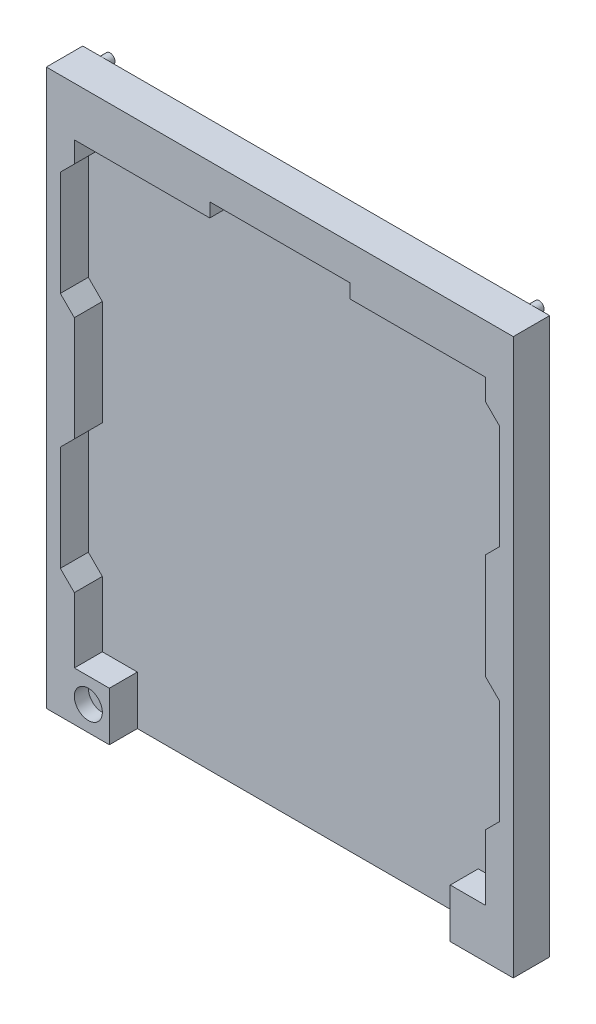
SolidWorks part; units mm, degrees
ref_plane "Plan de face" through (0, 0, 0) normal (0, 0, 1) x (1, 0, 0)
ref_plane "Plan de dessus" through (0, 0, 0) normal (0, 1, 0) x (1, 0, 0)
ref_plane "Plan de droite" through (0, 0, 0) normal (1, 0, 0) x (0, 0, -1)
sketch "Esquisse1" plane through (0, 0, 0) normal (0, 0, 1) x (1, 0, 0)
  line L1 (-33.34, 39.66) -> (0, 39.66)
  line L2 (-33.34, 39.66) -> (-33.34, 0)
  line L3 (-33.34, 0) -> (0, 0)
  line L4 (0, 39.66) -> (0, 0)
  dimension "D1" = 39.66
  dimension "D2" = 33.34
extrude "Boss.-Extru.1" add sketch "Esquisse1" along normal blind 0.6
sketch "Esquisse2" plane through (0, 0, 0.6) normal (0, 0, 1) x (1, 0, 0)
  line L0 (-31.34, 36.16) -> (-21.67, 36.16)
  line L1 (-33.34, 39.66) -> (0, 39.66)
  line L2 (-33.34, 39.66) -> (-33.34, 0)
  line L3 (-33.34, 0) -> (0, 0)
  line L4 (0, 39.66) -> (0, 0)
  line L5 (-21.67, 36.16) -> (-21.67, 37.16)
  line L6 (-2, 36.16) -> (-11.67, 36.16)
  line L7 (-11.67, 36.16) -> (-11.67, 37.16)
  line L8 (-11.67, 37.16) -> (-21.67, 37.16)
  line L9 (-2, 36.16) -> (-2, 34.66)
  line L10 (-31.34, 36.16) -> (-31.34, 34.66)
  line L11 (-1, 33.66) -> (-1, 26.16)
  line L12 (-31.34, 25.16) -> (-32.34, 26.16)
  line L13 (-2, 25.16) -> (-2, 17.66)
  line L14 (-2, 17.66) -> (-1, 16.66)
  line L15 (-1, 16.66) -> (-1, 9.16)
  line L16 (-1, 9.16) -> (-2, 8.16)
  line L17 (-2, 8.16) -> (-2, 3.5)
  line L18 (-2, 3.5) -> (-4.5, 3.5)
  line L19 (-4.5, 3.5) -> (-4.5, 0)
  line L20 (-4.5, 0) -> (-28.84, 0)
  line L21 (-28.84, 0) -> (-28.84, 3.5)
  line L22 (-28.84, 3.5) -> (-31.34, 3.5)
  line L23 (-31.34, 3.5) -> (-31.34, 8.16)
  line L24 (-31.34, 8.16) -> (-32.34, 9.16)
  line L25 (-32.34, 9.16) -> (-32.34, 16.66)
  line L26 (-32.34, 16.66) -> (-31.34, 17.66)
  line L27 (-31.34, 17.66) -> (-31.34, 25.16)
  line L28 (-32.34, 26.16) -> (-32.34, 33.66)
  line L29 (-32.34, 33.66) -> (-31.34, 34.66)
  line L30 (-1, 26.16) -> (-2, 25.16)
  line L31 (-1, 33.66) -> (-2, 34.66)
  point P8 (-16.67, 37.16)
  line M1 (-33.34, 39.66) -> (-33.34, 0)
  line M2 (-33.34, 0) -> (0, 0)
  line M3 (0, 0) -> (0, 39.66)
  line M4 (0, 39.66) -> (-33.34, 39.66)
  dimension "D1" = 33.34
  dimension "D2" = 2
  dimension "D3" = 10
  dimension "D4" = 2.5
  dimension "D5" = 2
  dimension "D6" = 3.5
  dimension "D7" = 3.5
  dimension "D8" = 16.67
  dimension "D9" = 2
  dimension "D10" = 2
  dimension "D11" = 1
  dimension "D12" = 1
  dimension "D13" = 135
  dimension "D14" = 135
  dimension "D15" = 2
  dimension "D16" = 3.5
  dimension "D17" = 3.5
  dimension "D18" = 4.5
  dimension "D19" = 4.5
  dimension "D20" = 2
  dimension "D21" = 1
  dimension "D22" = 135
  dimension "D23" = 135
  dimension "D24" = 1
  dimension "D25" = 135
  dimension "D26" = 135
  dimension "D27" = 135
  dimension "D28" = 135
  dimension "D29" = 5
  dimension "D30" = 5
  dimension "D31" = 7.5
  dimension "D32" = 7.5
  dimension "D33" = 7.5
  dimension "D34" = 7.5
  dimension "D35" = 7.5
  dimension "D36" = 7.5
extrude "Boss.-Extru.2" add sketch "Esquisse2" along normal blind 2 contours L31 L11 L30 L13 L14 L15 L16 L17 L18 L19 L3 L21 L22 L23 L24 L25 L26 L27 L12 L28 L29 L10 L0 L5 L8 L7 L6 L9 M3 M4 M1 M2
sketch "Esquisse3" plane through (0, 0, 0) normal (0, 0, -1) x (-1, 0, 0)
  line L0 (0, 0) -> (0, 39.66) construction
  line L2 (0, 39.66) -> (33.34, 39.66) construction
  circle A0 centre (1.35, 39.26) radius 0.35
  circle A1 centre (31.99, 39.26) radius 0.35
  point P6 (0, 0)
  point P8 (0, 0)
  dimension "D1" = 0.7
  dimension "D2" = 0.7
  dimension "D3" = 30.64
  dimension "D4" = 1.35
  dimension "D5" = 0.4
extrude "Boss.-Extru.3" add sketch "Esquisse3" along normal blind 0.6
sketch "Esquisse4" plane through (0, 0, 2.6) normal (0, 0, 1) x (1, 0, 0)
  line L0 (-33.34, 0) -> (-28.84, 0) construction
  line L1 (-33.34, 39.66) -> (-33.34, 0) construction
  circle A0 centre (-30.34, 1.75) radius 1
  point P4 (-31.09, 0)
  dimension "D1" = 2
  dimension "D2" = 1.75
  dimension "D3" = 3
extrude "Enlèv. mat.-Extru.1" cut sketch "Esquisse4" against normal blind 1
